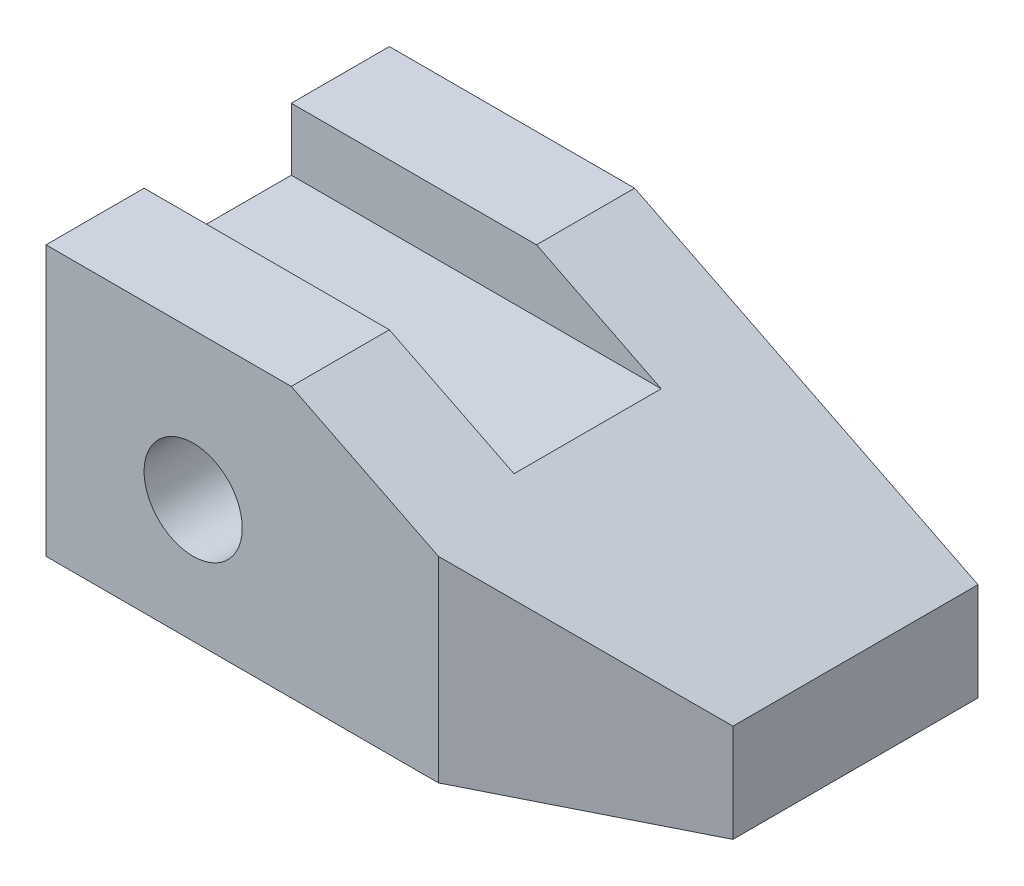
SolidWorks part; units mm, degrees
ref_plane "Front Plane" through (0, 0, 0) normal (0, 0, 1) x (1, 0, 0)
ref_plane "Top Plane" through (0, 0, 0) normal (0, 1, 0) x (1, 0, 0)
ref_plane "Right Plane" through (0, 0, 0) normal (1, 0, 0) x (0, 0, -1)
sketch "Sketch1" plane through (0, 0, 0) normal (0, 0, 1) x (1, 0, 0)
  line L0 (-125.52, 46.92) -> (26.88, 46.92)
  line L1 (26.88, 46.92) -> (26.88, 72.32)
  line L2 (-125.52, 46.92) -> (-125.52, 116.77)
  line L3 (-125.52, 116.77) -> (-62.02, 116.77)
  line L4 (-62.02, 116.77) -> (26.88, 72.32)
  circle A0 centre (-87.42, 78.67) radius 12.7
  dimension "D5" = 25.4
  dimension "D1" = 152.4
  dimension "D2" = 69.85
  dimension "D3" = 63.5
  dimension "D4" = 25.4
  dimension "D6" = 31.75
  dimension "D7" = 38.1
extrude "Boss-Extrude1" add sketch "Sketch1" along normal blind 88.9
sketch "Sketch2" plane through (0, 116.77, 0) normal (0, 1, 0) x (1, 0, 0)
  line L0 (26.88, -63.4514) -> (-23.92, -88.9)
  line L1 (26.88, -88.9) -> (26.88, 0) construction
  line L2 (26.88, -88.9) -> (-62.02, -88.9) construction
  line L3 (26.88, -63.4514) -> (26.88, -88.9)
  line L4 (26.88, -88.9) -> (-23.92, -88.9)
  dimension "D1" = 63.4514
  dimension "D2" = 101.6
extrude "Cut-Extrude1" cut sketch "Sketch2" against normal through all
sketch "Sketch3" plane through (-125.52, 0, 0) normal (-1, 0, 0) x (0, 0, 1)
  line L0 (88.9, 116.77) -> (0, 116.77) construction
  line L1 (25.4, 116.77) -> (63.5, 116.77)
  line L2 (25.4, 116.77) -> (25.4, 100.6314)
  line L3 (25.4, 100.6314) -> (63.5, 100.6314)
  line L4 (63.5, 116.77) -> (63.5, 100.6314)
  line L5 (0, 116.77) -> (0, 46.92) construction
  dimension "D1" = 25.4
  dimension "D2" = 38.1
extrude "Cut-Extrude2" cut sketch "Sketch3" against normal blind 254
